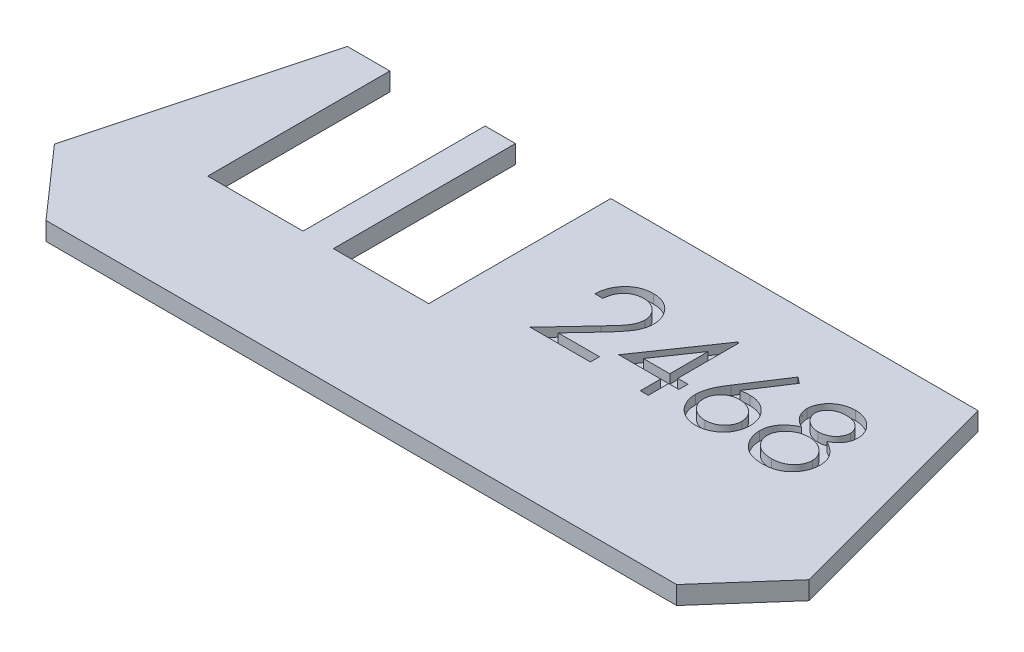
SolidWorks part; units mm, degrees
ref_plane "Front Plane" through (0, 0, 0) normal (0, 0, 1) x (1, 0, 0)
ref_plane "Top Plane" through (0, 0, 0) normal (0, 1, 0) x (1, 0, 0)
ref_plane "Right Plane" through (0, 0, 0) normal (1, 0, 0) x (0, 0, -1)
sketch "Sketch1" plane through (0, 0, 0) normal (0, 1, 0) x (1, 0, 0)
  line L0 (-26.3906, 12.6111) -> (-31.5722, -6.7269)
  line L1 (-26.3906, -12.6111) -> (26.3906, -12.6111)
  line L2 (-26.3906, -12.6111) -> (-26.3906, 12.6111) construction
  line L3 (-26.3906, 12.6111) -> (26.3906, 12.6111)
  line L4 (26.3906, -12.6111) -> (26.3906, 12.6111) construction
  line L5 (-26.3906, -12.6111) -> (26.3906, 12.6111) construction
  line L6 (-26.3906, 12.6111) -> (26.3906, -12.6111) construction
  line L7 (-31.5722, -6.7269) -> (-26.3906, -12.6111)
  line L8 (26.3906, -12.6111) -> (31.5722, -6.7269)
  line L9 (31.5722, -6.7269) -> (26.3906, 12.6111)
  point P0 (0, 0)
  dimension "D1" = 25.2222
  dimension "D2" = 52.7812
  dimension "D3" = 63.1444
  dimension "D4" = 15
  dimension "D5" = 15
extrude "Boss-Extrude1" add sketch "Sketch1" along normal blind 1.524
sketch "Sketch3" plane through (0, 1.524, 0) normal (0, 1, 0) x (1, 0, 0)
  line L0 (26.3906, 12.6111) -> (-26.3906, 12.6111) construction
  line L1 (-22.8346, 12.6111) -> (-14.859, 12.6111)
  line L2 (-22.8346, 12.6111) -> (-22.8346, -2.6289)
  line L3 (-22.8346, -2.6289) -> (-14.859, -2.6289)
  line L4 (-14.859, 12.6111) -> (-14.859, -2.6289)
  line L6 (-12.319, 12.6111) -> (-4.3434, 12.6111)
  line L7 (-12.319, 12.6111) -> (-12.319, -2.6289)
  line L8 (-12.319, -2.6289) -> (-4.3434, -2.6289)
  line L9 (-4.3434, 12.6111) -> (-4.3434, -2.6289)
  dimension "D1" = 7.9756
  dimension "D2" = 15.24
  dimension "D3" = 3.556
  dimension "D4" = 2.54
extrude "Cut-Extrude1" cut sketch "Sketch3" against normal up to next
sketch "Sketch2" plane through (0, 1.524, 0) normal (0, 1, 0) x (1, 0, 0)
  line L0 (-4.3434, -0.0889) -> (29.7936, -0.0889) construction
  line L1 (-4.3434, -2.6289) -> (-4.3434, 12.6111) construction
  line L2 (31.5722, -6.7269) -> (26.3906, 12.6111) construction
  line L3 (-12.319, -2.6289) -> (-4.3434, -2.6289) construction
  text T0 "2468" font "Century Gothic" height in points 28
  dimension "D1" = 2.54
extrude "Cut-Extrude2" cut sketch "Sketch2" against normal blind 0.762
